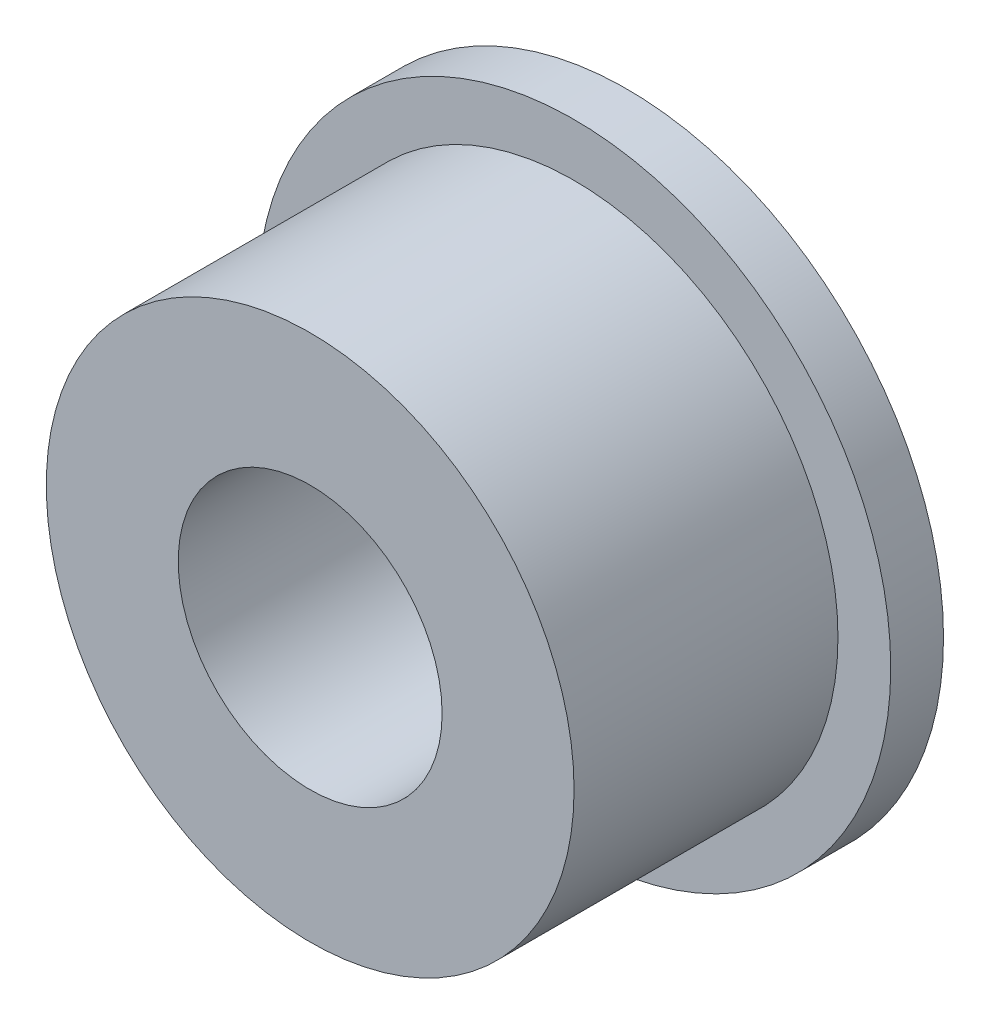
SolidWorks part; units mm, degrees
ref_plane "up基准面" through (0, 0, 0) normal (0, 0, 1) x (1, 0, 0)
ref_plane "前基准面" through (0, 0, 0) normal (0, 1, 0) x (1, 0, 0)
ref_plane "右视基准面" through (0, 0, 0) normal (1, 0, 0) x (0, 0, -1)
sketch "草图8" plane through (0, 0, 0) normal (0, 1, 0) x (1, 0, 0)
  line L0 (25, -60) -> (25, -20)
  line L1 (0, 0) -> (60, 0)
  line L2 (25, -20) -> (0, -20)
  line L3 (25, -60) -> (50, -60)
  line L4 (50, -10) -> (50, -60)
  line L5 (0, -20) -> (0, 0)
  line L8 (60, 0) -> (60, -10)
  line L9 (60, -10) -> (50, -10)
  dimension "D1" = 60
  dimension "D2" = 25
  dimension "D4" = 50
  dimension "D5" = 10
revolve "旋转1" add sketch "草图8" angle 360 about L5
